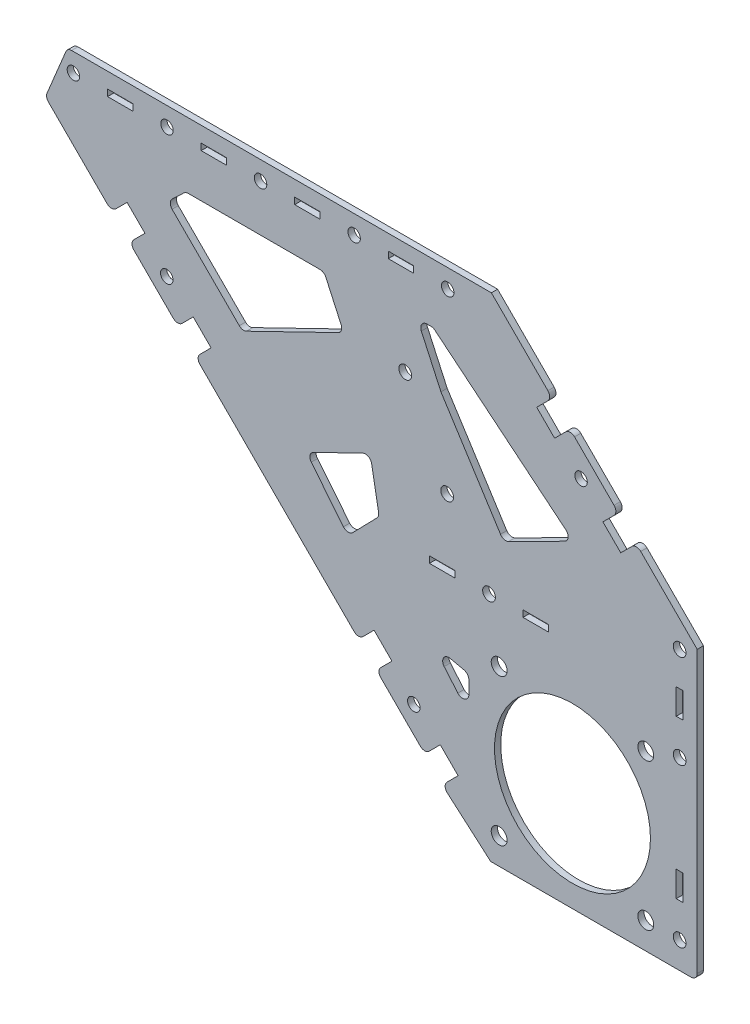
SolidWorks part; units mm, degrees
ref_plane "前视基准面" through (0, 0, 0) normal (0, 0, 1) x (1, 0, 0)
ref_plane "上视基准面" through (0, 0, 0) normal (0, 1, 0) x (1, 0, 0)
ref_plane "右视基准面" through (0, 0, 0) normal (1, 0, 0) x (0, 0, -1)
sketch "草图1" plane through (0, 0, 0) normal (0, 0, 1) x (1, 0, 0)
  line L261 (47.0274, 35.0547) -> (47.0274, 15.0547) construction
  line L315 (7.0274, -4.999) -> (20.8108, -16.957)
  line L316 (-52.9726, 135.0547) -> (-52.9726, 126.7057) construction
  line L332 (-112.9726, 135.0547) -> (-97.9726, 135.0547) construction
  line L334 (-42.0226, 136.1047) -> (-33.9226, 136.1047)
  line L335 (-42.0226, 136.1047) -> (-42.0226, 134.0047)
  line L336 (-42.0226, 134.0047) -> (-33.9226, 134.0047)
  line L337 (-33.9226, 136.1047) -> (-33.9226, 134.0047)
  line L338 (-42.0226, 136.1047) -> (-33.9226, 134.0047) construction
  line L339 (-42.0226, 134.0047) -> (-33.9226, 136.1047) construction
  line L389 (-114.8842, 141.0547) -> (21.0274, 141.0547)
  line L390 (-22.9726, 135.0547) -> (-22.9726, 144.5851) construction
  line L395 (-37.9726, 135.0547) -> (-7.9726, 135.0547) construction
  line L418 (87.0274, 75.0547) -> (21.0274, 141.0547) construction
  line L419 (-3.9226, 134.0047) -> (-12.0226, 136.1047) construction
  line L420 (-3.9226, 136.1047) -> (-12.0226, 134.0047) construction
  line L421 (7.0274, 135.0547) -> (-7.9726, 135.0547) construction
  line L422 (-12.0226, 136.1047) -> (-12.0226, 134.0047)
  line L423 (-3.9226, 134.0047) -> (-12.0226, 134.0047)
  line L424 (-3.9226, 136.1047) -> (-3.9226, 134.0047)
  line L443 (-3.9226, 136.1047) -> (-12.0226, 136.1047)
  line L444 (-102.0226, 136.1047) -> (-93.9226, 134.0047) construction
  line L445 (-102.0226, 134.0047) -> (-93.9226, 136.1047) construction
  line L447 (-67.9726, 135.0547) -> (-97.9726, 135.0547) construction
  line L448 (-104.2577, 114.7679) -> (-83.0445, 93.5547) construction
  line L449 (-63.9226, 134.0047) -> (-72.0226, 136.1047) construction
  line L483 (-63.9226, 136.1047) -> (-72.0226, 134.0047) construction
  line L515 (47.0274, 35.0547) -> (47.0274, 135.0547) construction
  line L516 (47.0274, 135.0547) -> (-52.9726, 135.0547) construction
  line L517 (-102.0226, 136.1047) -> (-93.9226, 136.1047)
  line L518 (-102.0226, 136.1047) -> (-102.0226, 134.0047)
  line L519 (-102.0226, 134.0047) -> (-93.9226, 134.0047)
  line L520 (-93.9226, 136.1047) -> (-93.9226, 134.0047)
  line L521 (-72.0226, 136.1047) -> (-72.0226, 134.0047)
  line L522 (-63.9226, 134.0047) -> (-72.0226, 134.0047)
  line L523 (-63.9226, 136.1047) -> (-63.9226, 134.0047)
  line L524 (-63.9226, 136.1047) -> (-72.0226, 136.1047)
  line L556 (21.4033, 132.1936) -> (81.3921, 72.2048) construction
  line L557 (54.0274, 108.0547) -> (35.0674, 89.0947) construction
  line L558 (42.7844, 112.2974) -> (35.5719, 116.54) construction
  line L559 (56.7851, 95.3268) -> (62.5127, 89.5993)
  line L576 (56.7851, 95.3268) -> (58.2701, 96.8117)
  line L577 (58.2701, 96.8117) -> (63.9976, 91.0842) construction
  line L578 (62.5127, 89.5993) -> (63.9976, 91.0842)
  line L579 (56.7851, 95.3268) -> (63.9976, 91.0842) construction
  line L580 (58.2701, 96.8117) -> (62.5127, 89.5993) construction
  line L581 (41.2995, 110.8124) -> (37.0569, 118.0249) construction
  line L582 (35.5719, 116.54) -> (37.0569, 118.0249)
  line L583 (42.7844, 112.2974) -> (37.0569, 118.0249) construction
  line L584 (41.2995, 110.8124) -> (42.7844, 112.2974)
  line L585 (41.2995, 110.8124) -> (35.5719, 116.54)
  line L586 (60.3914, 93.2055) -> (59.6489, 92.463) construction
  line L587 (39.1782, 114.4187) -> (38.4357, 113.6762) construction
  line L589 (20.2758, 57.0547) -> (5.2758, 57.0547) construction
  line L605 (-26.0184, 28.0504) -> (-21.7793, 32.2895) construction
  line L607 (-83.0445, 93.5547) -> (-87.2854, 89.3138) construction
  line L621 (-83.0445, 93.5547) -> (-61.8313, 72.3415) construction
  line L623 (73.2276, -16.9644) -> (87.0274, -16.9644)
  line L624 (23.5274, -8.4453) -> (70.5274, -8.4453) construction
  line L631 (-97.2574, 106.2827) -> (-91.5298, 100.5551) construction
  line L632 (-82.9726, 135.0547) -> (-82.9726, 64.2144) construction
  line L633 (-97.2574, 106.2827) -> (-95.7724, 107.7676)
  line L638 (-22.9726, 135.0547) -> (-22.9726, 124.9547) construction
  line L639 (87.0274, -16.9644) -> (87.0274, 75.0547)
  line L640 (20.2758, 57.0547) -> (20.2758, 57.6954) construction
  line L641 (9.3758, 56.0047) -> (1.1758, 56.0047)
  line L642 (9.3758, 56.0047) -> (9.3758, 58.1047)
  line L643 (9.3758, 58.1047) -> (1.1758, 58.1047)
  line L644 (1.1758, 56.0047) -> (1.1758, 58.1047)
  line L645 (9.3758, 56.0047) -> (1.1758, 58.1047) construction
  line L646 (9.3758, 58.1047) -> (1.1758, 56.0047) construction
  line L647 (31.1758, 58.1047) -> (39.3758, 56.0047) construction
  line L648 (31.1758, 56.0047) -> (39.3758, 58.1047) construction
  line L649 (39.3758, 56.0047) -> (39.3758, 58.1047)
  line L650 (31.1758, 58.1047) -> (39.3758, 58.1047)
  line L651 (31.1758, 56.0047) -> (31.1758, 58.1047)
  line L652 (31.1758, 56.0047) -> (39.3758, 56.0047)
  line L653 (-6.5853, 99.2267) -> (-61.8313, 72.3415) construction
  line L654 (-104.2577, 114.7679) -> (-82.9726, 135.0547) construction
  line L655 (-82.9726, 135.0547) -> (-22.9726, 135.0547) construction
  line L656 (-22.9726, 135.0547) -> (-6.5853, 99.2267) construction
  line L657 (-61.8313, 72.3415) -> (-104.2577, 114.7679) construction
  line L658 (-26.3178, 106.3059) -> (-58.7833, 90.5067)
  line L659 (-58.7833, 90.5067) -> (-82.7867, 114.5102)
  line L660 (-82.7867, 114.5102) -> (-76.9693, 120.0547)
  line L661 (-76.9693, 120.0547) -> (-32.6063, 120.0547)
  line L662 (-32.6063, 120.0547) -> (-26.3178, 106.3059)
  line L663 (70.998, 82.5989) -> (20.2758, 57.0547) construction
  line L664 (70.998, 82.5989) -> (7.0274, 135.0547) construction
  line L665 (7.0274, 135.0547) -> (-22.9726, 135.0547) construction
  line L667 (47.2997, 85.2197) -> (24.9262, 73.9522)
  line L668 (4.8626, 105.452) -> (24.9262, 73.9522)
  line L669 (-2.7313, 122.0547) -> (4.8626, 105.452)
  line L670 (2.3789, 122.0547) -> (-2.7313, 122.0547)
  line L671 (47.2997, 85.2197) -> (2.3789, 122.0547)
  line L672 (1.1758, 56.0047) -> (-6.5853, 99.2267) construction
  line L673 (-61.8313, 72.3415) -> (-26.0184, 28.0504) construction
  line L674 (-26.0184, 28.0504) -> (1.1758, 56.0047) construction
  line L675 (-14.9502, 60.9397) -> (-17.8458, 77.065)
  line L676 (-17.8458, 77.065) -> (-38.3086, 67.1069)
  line L677 (-38.3086, 67.1069) -> (-24.9829, 50.6265)
  line L678 (-24.9829, 50.6265) -> (-14.9502, 60.9397)
  line L679 (23.8026, -6.8752) -> (23.8026, 39.5844) construction
  line L680 (23.8026, 39.5844) -> (-24.9829, 50.6265) construction
  line L681 (-24.9829, 50.6265) -> (23.8026, -6.8752) construction
  line L682 (2.0144, 34.263) -> (13.8026, 20.3686)
  line L683 (13.8026, 20.3686) -> (13.8026, 31.5948)
  line L684 (13.8026, 31.5948) -> (2.0144, 34.263)
  line L685 (23.5274, -8.4453) -> (23.5274, 38.5547) construction
  line L686 (23.5274, 38.5547) -> (70.5274, 38.5547) construction
  line L687 (70.5274, -8.4453) -> (70.5274, 38.5547) construction
  line L688 (23.5274, -8.4453) -> (70.5274, 38.5547) construction
  line L689 (23.5274, 38.5547) -> (70.5274, -8.4453) construction
  line L690 (-91.5298, 100.5551) -> (-90.0449, 102.04)
  line L691 (-95.7724, 107.7676) -> (-90.0449, 102.04)
  line L692 (-97.2574, 106.2827) -> (-90.0449, 102.04) construction
  line L693 (-91.5298, 100.5551) -> (-95.7724, 107.7676) construction
  line L694 (-76.0442, 85.0695) -> (-68.8317, 80.8268) construction
  line L695 (-70.3166, 79.3419) -> (-74.5592, 86.5544) construction
  line L696 (-68.8317, 80.8268) -> (-74.5592, 86.5544)
  line L697 (-76.0442, 85.0695) -> (-74.5592, 86.5544)
  line L698 (-70.3166, 79.3419) -> (-68.8317, 80.8268)
  line L699 (-70.3166, 79.3419) -> (-76.0442, 85.0695) construction
  line L700 (-70.3166, 79.3419) -> (-73.815, 75.8434)
  line L701 (-76.0442, 85.0695) -> (-79.5426, 81.571)
  line L702 (-91.5298, 100.5551) -> (-95.0283, 97.0566)
  line L703 (-97.2574, 106.2827) -> (-100.7558, 102.7842)
  line L704 (-121.9553, 123.9837) -> (-100.7558, 102.7842)
  line L705 (-95.0283, 97.0566) -> (-87.2854, 89.3138)
  line L706 (-87.2854, 89.3138) -> (-79.5426, 81.571)
  line L708 (37.0569, 118.0249) -> (40.557, 121.5251)
  line L709 (40.557, 121.5251) -> (21.0274, 141.0547)
  line L710 (42.7844, 112.2974) -> (46.2846, 115.7976)
  line L711 (46.2846, 115.7976) -> (54.0274, 108.0547)
  line L712 (54.0274, 108.0547) -> (61.7717, 100.3104)
  line L713 (61.7717, 100.3104) -> (58.2701, 96.8117)
  line L714 (63.9976, 91.0842) -> (67.4978, 94.5844)
  line L715 (67.4978, 94.5844) -> (87.0274, 75.0547)
  line L716 (20.8108, -16.957) -> (73.2276, -16.9644)
  line L717 (-6.5853, 99.2267) -> (20.2758, 57.0547) construction
  line L719 (81.3921, -8.4453) -> (81.3921, 72.2048) construction
  line L721 (-121.9553, 123.9837) -> (-114.8842, 141.0547)
  line L722 (80.2921, 53.1048) -> (82.4921, 53.1048)
  line L723 (80.2921, 53.1048) -> (80.2921, 61.3048)
  line L724 (80.2921, 61.3048) -> (82.4921, 61.3048)
  line L725 (82.4921, 53.1048) -> (82.4921, 61.3048)
  line L726 (80.2921, 53.1048) -> (82.4921, 61.3048) construction
  line L727 (80.2921, 61.3048) -> (82.4921, 53.1048) construction
  line L728 (80.2921, 2.4547) -> (82.4921, 2.4547)
  line L729 (80.2921, 2.4547) -> (80.2921, 10.6547)
  line L730 (80.2921, 10.6547) -> (82.4921, 10.6547)
  line L731 (82.4921, 2.4547) -> (82.4921, 10.6547)
  line L732 (80.2921, 2.4547) -> (82.4921, 10.6547) construction
  line L733 (80.2921, 10.6547) -> (82.4921, 2.4547) construction
  line L734 (-6.5853, 99.2267) -> (20.2758, 57.0547) construction
  line L735 (-47.6875, 49.7158) -> (-42.0122, 55.3911) construction
  line L736 (3.1518, 5.8735) -> (10.3643, 1.6309) construction
  line L737 (8.8794, 0.1459) -> (4.6367, 7.3584) construction
  line L738 (8.8794, 0.1459) -> (3.1518, 5.8735) construction
  line L739 (17.3646, -6.8544) -> (-3.8486, 14.3588) construction
  line L740 (-0.3467, 2.375) -> (-8.0895, 10.1179)
  line L741 (-21.5599, 23.5882) -> (-73.815, 75.8434)
  line L742 (8.8794, 0.1459) -> (5.3809, -3.3525)
  line L743 (3.1518, 5.8735) -> (-0.3467, 2.375)
  line L744 (10.3643, 1.6309) -> (4.6367, 7.3584)
  line L745 (3.1518, 5.8735) -> (4.6367, 7.3584)
  line L746 (8.8794, 0.1459) -> (10.3643, 1.6309)
  line L747 (-18.0614, 27.0867) -> (-12.3338, 21.3591) construction
  line L748 (-18.0614, 27.0867) -> (-10.8489, 22.8441) construction
  line L749 (-12.3338, 21.3591) -> (-16.5765, 28.5716) construction
  line L750 (-25.0618, 35.572) -> (17.3646, -6.8544) construction
  line L751 (-3.8486, 14.3588) -> (-25.0618, 35.572) construction
  line L752 (5.3809, -3.3525) -> (7.0274, -4.999)
  line L753 (-6.5853, 99.2267) -> (-6.5853, 105.2267) construction
  line L754 (-8.0895, 10.1179) -> (-15.8323, 17.8607)
  line L755 (-12.3338, 21.3591) -> (-15.8323, 17.8607)
  line L756 (-18.0614, 27.0867) -> (-21.5599, 23.5882)
  line L757 (-18.0614, 27.0867) -> (-16.5765, 28.5716)
  line L758 (-12.3338, 21.3591) -> (-10.8489, 22.8441)
  line L759 (-16.5765, 28.5716) -> (-10.8489, 22.8441)
  circle A39 centre (-52.9726, 135.0547) radius 2
  circle A42 centre (47.0274, 15.0547) radius 25
  circle A49 centre (-22.9726, 135.0547) radius 2
  circle A69 centre (7.0274, 135.0547) radius 2
  circle A92 centre (-112.9726, 135.0547) radius 2
  circle A93 centre (-82.9726, 135.0547) radius 2
  circle A98 centre (49.7848, 103.8121) radius 2
  arc A115 (-114.8842, 141.0547) -> (-121.9553, 123.9837) centre (-114.8842, 131.0547) ccw construction
  circle A116 centre (-83.0445, 93.5547) radius 2
  circle A121 centre (20.2758, 57.0547) radius 2.05
  circle A122 centre (-6.5853, 99.2267) radius 2.05 construction
  circle A123 centre (70.5274, -8.4453) radius 2.55
  circle A124 centre (23.5274, -8.4453) radius 2.55
  circle A125 centre (23.5274, 38.5547) radius 2.55
  circle A126 centre (70.5274, 38.5547) radius 2.55
  circle A127 centre (81.3921, 72.2048) radius 2.05
  circle A128 centre (81.3921, -8.4453) radius 2.05
  circle A129 centre (81.3921, 42.2048) radius 2.05
  circle A130 centre (6.8453, 78.1407) radius 2.05
  circle A131 centre (-3.8486, 14.3588) radius 2
  circle A132 centre (-6.5853, 105.2267) radius 2.05
  point P5 (210.9534, 218.4629)
  point P6 (288.6284, 218.4629)
  point P51 (-93.6511, 104.1613)
  point P54 (-105.4726, 135.0547)
  point P60 (60.3914, 93.2055)
  point P83 (-93.6511, 104.1613)
  point P98 (81.3921, 57.2048)
  point P115 (47.016, -39.6917)
  point P147 (-72.4379, 82.9481)
  point P152 (81.3921, 6.5547)
  point P173 (6.758, 3.7522)
  point P183 (-14.4552, 24.9654)
  dimension "D3" = 50
  dimension "D5" = 4
  dimension "D4" = 47
  dimension "D6" = 15
  dimension "D7" = 2.1
  dimension "D12" = 4
  dimension "D19" = 29.4043
  dimension "D20" = 2.2
  dimension "D22" = 4
  dimension "D8" = 30
  dimension "D28" = 8.2
  dimension "D26" = 10
  dimension "D17" = 10.1
  dimension "D29" = 42
  dimension "D30" = 15
  dimension "D31" = 80.6501
  dimension "D18" = 8.1
  dimension "D15" = 8.2
  dimension "D27" = 30
  dimension "D40" = 56
  dimension "D9" = 15
  dimension "D10" = 15
  dimension "D11" = 8.1
  dimension "D13" = 2.1
  dimension "D14" = 6
  dimension "D16" = 41.5
  dimension "D21" = 6
  dimension "D23" = 15
  dimension "D24" = 15
  dimension "D25" = 2.1
  dimension "D32" = 8.2
  dimension "D33" = 2.1
  dimension "D34" = 120
  dimension "D35" = 70
  dimension "D36" = 15
  dimension "D37" = 13
  dimension "D38" = 15
  dimension "D39" = 10
extrude "凸台-拉伸1" add sketch "草图1" along normal blind 2
fillet "圆角2" radius 2 31 edges at (-76.9693, 120.0547, 1) (-82.7867, 114.5102, 1) (-32.6063, 120.0547, 1) (-26.3178, 106.3059, 1) (-58.7833, 90.5067, 1) (-17.8458, 77.065, 1) (-14.9502, 60.9397, 1) (-24.9829, 50.6265, 1) (-38.3086, 67.1069, 1) (47.2997, 85.2197, 1) (24.9262, 73.9522, 1) (2.3789, 122.0547, 1) (-2.7313, 122.0547, 1) (13.8026, 31.5948, 1) (2.0144, 34.263, 1) (13.8026, 20.3686, 1) (87.0274, -16.9644, 1) (-100.7558, 102.7842, 1) (-95.0283, 97.0566, 1) (-79.5426, 81.571, 1) (67.4978, 94.5844, 1) (61.7717, 100.3104, 1) (46.2846, 115.7976, 1) (40.557, 121.5251, 1) (-114.8842, 141.0547, 1) (-121.9553, 123.9837, 1) (5.3809, -3.3525, 1) (-0.3467, 2.375, 1) (-15.8323, 17.8607, 1) (-21.5599, 23.5882, 1) (-73.815, 75.8434, 1)
